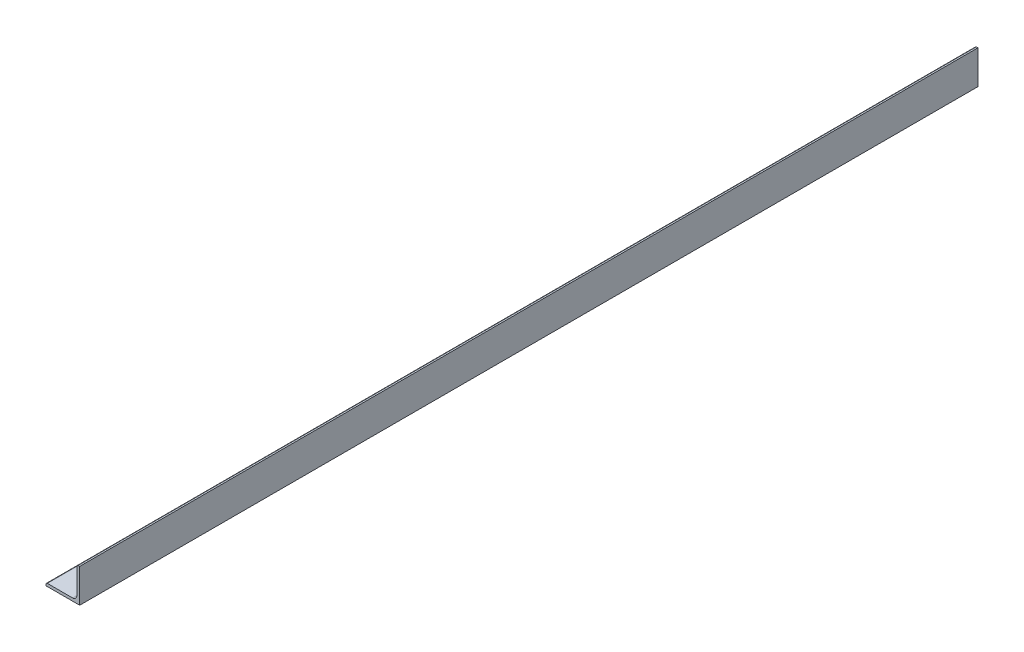
SolidWorks part; units mm, degrees
ref_plane "Front Plane" through (0, 0, 0) normal (0, 0, 1) x (1, 0, 0)
ref_plane "Top Plane" through (0, 0, 0) normal (0, 1, 0) x (1, 0, 0)
ref_plane "Right Plane" through (0, 0, 0) normal (1, 0, 0) x (0, 0, -1)
sketch "Sketch0" plane through (0, 0, 0) normal (0, 0, 1) x (1, 0, 0)
  line L0 (-9.525, -9.525) -> (9.525, -9.525)
  line L1 (9.525, -9.525) -> (9.525, 9.525)
  line L2 (9.525, 0) -> (0, 0) construction
  line L3 (0, 0) -> (0, -9.525) construction
  line L4 (7.9375, -5.5499) -> (7.9375, 9.525) construction
  line L5 (5.5499, -7.9375) -> (-9.525, -7.9375) construction
  arc A0 (7.9375, -5.5499) -> (5.5499, -7.9375) centre (5.5499, -5.5499) cw
  point P3 (7.2382, -7.2382)
  dimension "Inside Corner Radius" = 2.3876
  dimension "Outside Height" = 19.05
  dimension "Inside Height" = 17.4625
  dimension "Inside Width" = 17.4625
  dimension "Wall Thickness" = 1.5875
  dimension "D1" = 1.5875
  dimension "Outside Width" = 19.05
sketch "Sketch1" plane through (0, 0, 0) normal (1, 0, 0) x (0, 0, -1)
  line L0 (254, 0) -> (-254, 0)
  point P4 (0, 0)
  dimension "Length" = 508
sketch "Sketch2" plane through (0, 0, 0) normal (0, 0, 1) x (1, 0, 0)
  line L0 (-9.525, -9.525) -> (9.525, -9.525)
  line L1 (9.525, -9.525) -> (9.525, 9.525)
  line L2 (9.525, 9.525) -> (7.9375, 9.525) construction
  line L3 (7.9375, 8.7313) -> (7.9375, -5.5499)
  line L4 (5.5499, -7.9375) -> (-8.7313, -7.9375)
  line L5 (-9.525, -9.525) -> (-9.525, -7.9375) construction
  line L6 (8.7313, 9.525) -> (9.525, 9.525)
  line L7 (-9.525, -8.7313) -> (-9.525, -9.525)
  line L8 (9.525, 0) -> (0, 0) construction
  line L9 (0, 0) -> (0, -9.525) construction
  arc A0 (7.9375, 8.7313) -> (8.7313, 9.525) centre (8.7313, 8.7313) cw
  arc A1 (-9.525, -8.7313) -> (-8.7313, -7.9375) centre (-8.7313, -8.7313) cw
  arc A2 (7.9375, -5.5499) -> (5.5499, -7.9375) centre (5.5499, -5.5499) cw
  dimension "Inside Radius" = 2.3876
  dimension "Height" = 19.05
  dimension "Width" = 19.05
  dimension "Thickness" = 1.5875
extrude "Boss-Extrude1" add sketch "Sketch2" along normal mid plane 508
sketch "Break Locations" plane through (0, 0, 0) normal (1, 0, 0) x (0, 0, -1)
  line L0 (-234.569, 0) -> (234.569, 0)
  line L1 (-254, -9.525) -> (-254, 9.525) construction
  line L2 (254, -9.525) -> (254, 9.525) construction
  point P0 (-237.8075, 0)
  point P1 (237.8075, 0)
  point P10 (0, 0)
  point P11 (234.569, 0)
  point P13 (-234.569, 0)
  dimension "D1" = 16.1925
  dimension "D2" = 16.1925
  dimension "D3" = 19.431
equation "\"D1@Break Locations\" = .85 * \"Height@Sketch2\""
equation "\"D2@Break Locations\"=\"D1@Break Locations\""
equation "\"Thickness@Sketch2\"=\"wall thickness@sketch0\""
equation "\"Height@Sketch2\"=\"outside height@sketch0\""
equation "\"Width@Sketch2\"=\"outside width@sketch0\""
equation "\"Inside Radius@Sketch2\"=\"inside corner radius@sketch0\""
equation "\"Length@Boss-Extrude1\"=\"length@sketch1\""
equation "\"D3@Break Locations\"=\"D2@Break Locations\"*1.2"
equation "\"D1@Sketch0\"=\"Wall Thickness@Sketch0\""
